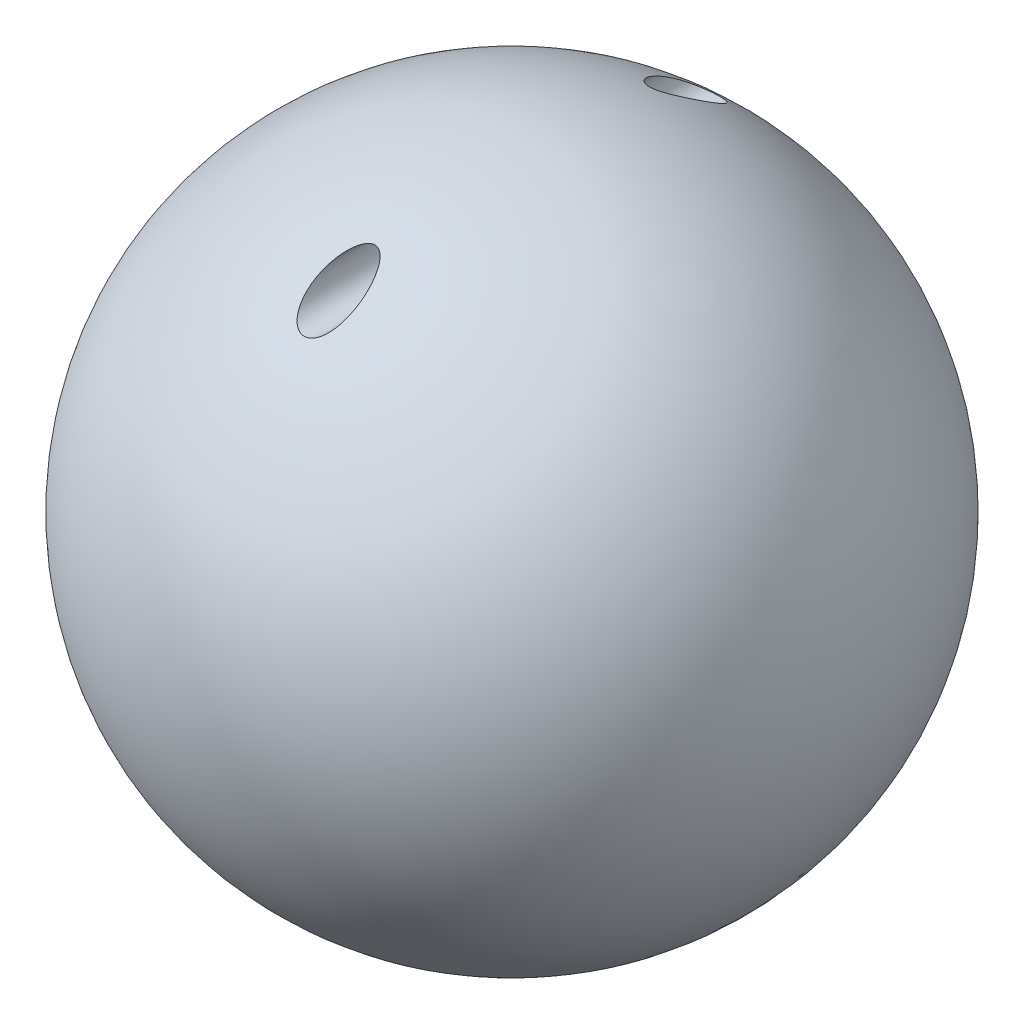
SolidWorks part; units mm, degrees
ref_plane "Front Plane" through (0, 0, 0) normal (0, 0, 1) x (1, 0, 0)
ref_plane "Top Plane" through (0, 0, 0) normal (0, 1, 0) x (1, 0, 0)
ref_plane "Right Plane" through (0, 0, 0) normal (1, 0, 0) x (0, 0, -1)
sketch "Sketch1" plane through (0, 0, 0) normal (0, 0, 1) x (1, 0, 0)
  line L0 (0, 0) -> (0, 76.2)
  arc A0 (0, 76.2) -> (0, 0) centre (0, 38.1) cw
  point P4 (0, 0)
  point P5 (0, 38.1)
  dimension "D1" = 76.2
revolve "Revolve1" add sketch "Sketch1" angle 360 about L0
sketch "Sketch2" plane through (0, 0, 0) normal (0, 0, 1) x (1, 0, 0)
sketch "Sketch5" plane through (0, 0, 0) normal (0, 0, 1) x (1, 0, 0)
  line L0 (0, 0) -> (0, 76.2) construction
  circle A0 centre (0, 70.2169) radius 2.5328
extrude "Cut-Extrude5" cut sketch "Sketch5" against normal through all both and the other way through all
